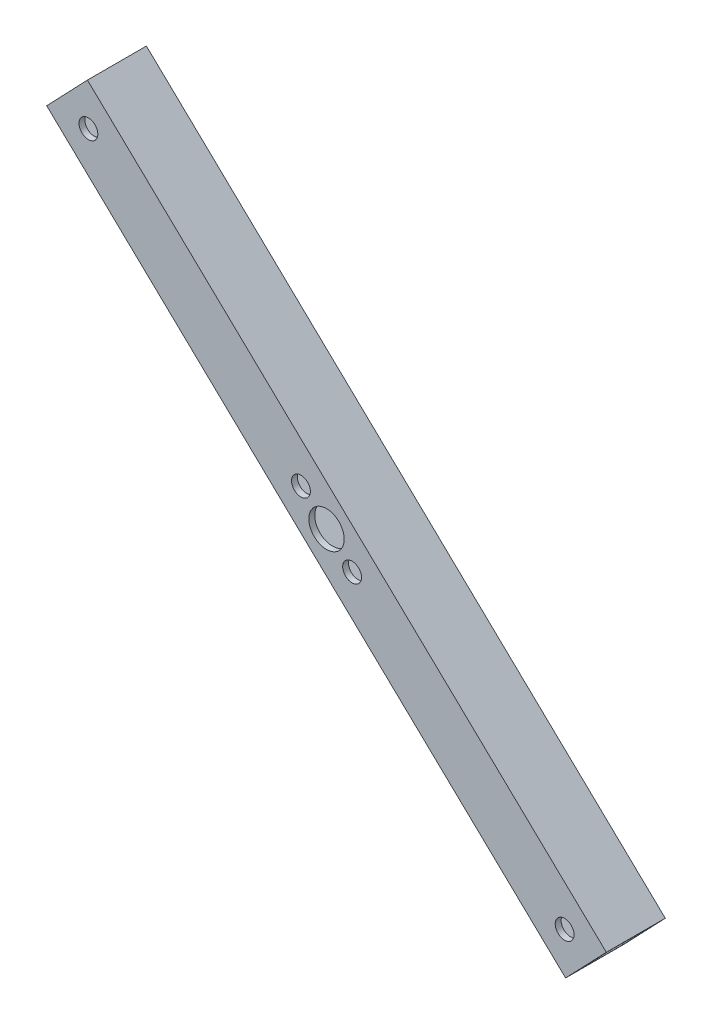
SolidWorks part; units mm, degrees
ref_plane "正面" through (0, 0, 0) normal (0, 0, 1) x (1, 0, 0)
ref_plane "平面" through (0, 0, 0) normal (0, 1, 0) x (1, 0, 0)
ref_plane "右側面" through (0, 0, 0) normal (1, 0, 0) x (0, 0, -1)
sketch "ｽｹｯﾁ2" plane through (0, 0, 0) normal (0, 0, 1) x (1, 0, 0)
  line L0 (-3.7761, 84.2848) -> (76.9904, 7.0917)
  line L1 (83.0716, 8.196) -> (-3.936, 91.3541)
  line L2 (-3.936, 91.3541) -> (-10.8454, 84.1249)
  line L3 (-10.8454, 84.1249) -> (77.1503, 0.0225)
  line L4 (77.1503, 0.0225) -> (84.0597, 7.2517)
  line L5 (84.0597, 7.2517) -> (83.0716, 8.196)
  circle A0 centre (-3.7761, 84.2848) radius 1.6
  circle A1 centre (76.9904, 7.0917) radius 1.6
  dimension "D1" = 111.7229
  dimension "D4" = 5
  dimension "D5" = 5
  dimension "D2" = 5
  dimension "D3" = 5
extrude "ﾎﾞｽ - 押し出し1" add sketch "ｽｹｯﾁ2" along normal blind 10
sketch "ｽｹｯﾁ3" plane through (40.3084, -38.525, 0) normal (0.7229, -0.6909, 0) x (0, 0, -1)
  line L0 (-10, 53.322) -> (0, 53.322) construction
  line L1 (-9, 54.322) -> (-1, 54.322)
  line L2 (-9, 54.322) -> (-9, 62.322)
  line L3 (-9, 62.322) -> (-1, 62.322)
  line L4 (-1, 54.322) -> (-1, 62.322)
  line L5 (-10, 53.322) -> (-10, 63.322) construction
  dimension "D1" = 1
  dimension "D2" = 1
  dimension "D3" = 8
  dimension "D4" = 8
extrude "ｶｯﾄ - 押し出し1" cut sketch "ｽｹｯﾁ3" against normal through all
sketch "ｽｹｯﾁ4" plane through (0, 0, 10) normal (0, 0, 1) x (1, 0, 0)
  line L0 (33.1525, 42.0737) -> (36.6072, 45.6883)
  line L1 (-10.8454, 84.1249) -> (77.1503, 0.0225) construction
  circle A0 centre (40.9447, 41.5427) radius 1.6
  circle A1 centre (32.2696, 49.8339) radius 1.6
  circle A2 centre (36.6072, 45.6883) radius 3
  dimension "D1" = 6
  dimension "D2" = 6
extrude "ｶｯﾄ - 押し出し2" cut sketch "ｽｹｯﾁ4" against normal blind 10
